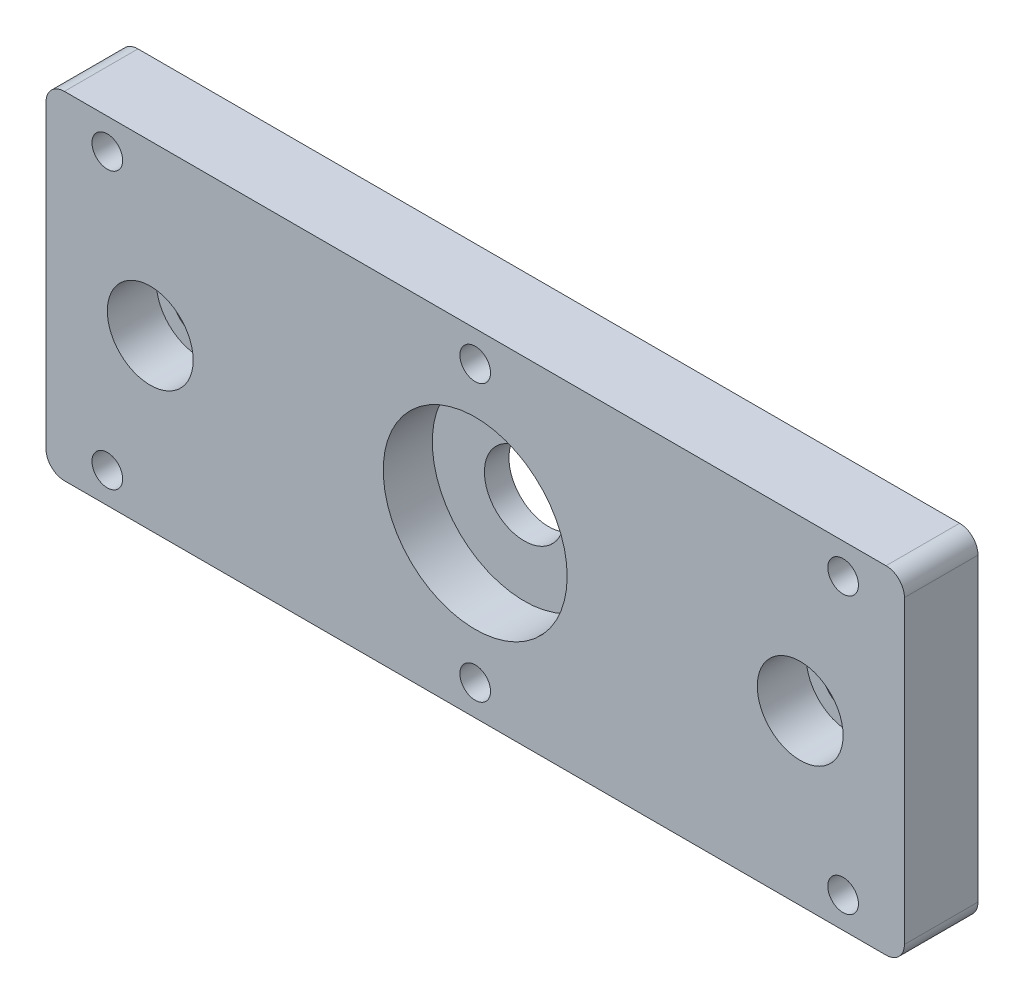
SolidWorks part; units mm, degrees
ref_plane "Front" through (0, 0, 0) normal (0, 0, 1) x (1, 0, 0)
ref_plane "Top" through (0, 0, 0) normal (0, 1, 0) x (1, 0, 0)
ref_plane "Right" through (0, 0, 0) normal (1, 0, 0) x (0, 0, -1)
sketch "草图1" plane through (0, 0, 0) normal (0, 0, 1) x (1, 0, 0)
  line L1 (-70, -27.5) -> (70, -27.5)
  line L2 (-70, -27.5) -> (-70, 27.5)
  line L3 (-70, 27.5) -> (70, 27.5)
  line L4 (70, -27.5) -> (70, 27.5)
  line L5 (-70, -27.5) -> (70, 27.5) construction
  line L6 (-70, 27.5) -> (70, -27.5) construction
  point P0 (0, 0)
  dimension "D1" = 55
  dimension "D2" = 140
extrude "凸台-拉伸1" add sketch "草图1" along normal blind 12
sketch "草图2" plane through (0, 0, 12) normal (0, 0, 1) x (1, 0, 0)
  line L0 (-70, 27.5) -> (-70, -27.5) construction
  line L1 (70, -27.5) -> (70, 27.5) construction
  circle A0 centre (0, 0) radius 6.5
  circle A1 centre (-53, 0) radius 4.5
  circle A2 centre (53, 0) radius 4.5
  dimension "D1" = 13
  dimension "D2" = 9
  dimension "D3" = 9
  dimension "D4" = 17
  dimension "D5" = 17
extrude "切除-拉伸1" cut sketch "草图2" against normal through all
fillet "圆角1" radius 3 4 edges at (70, 27.5, 6) (70, -27.5, 6) (-70, -27.5, 6) (-70, 27.5, 6)
sketch "草图10" plane through (0, 0, 12) normal (0, 0, 1) x (1, 0, 0)
  circle A0 centre (-53, 0) radius 7
  circle A1 centre (53, 0) radius 7
  dimension "D1" = 14
  dimension "D2" = 14
extrude "切除-拉伸2" cut sketch "草图10" against normal blind 8
sketch "草图11" plane through (0, 0, 12) normal (0, 0, 1) x (1, 0, 0)
  circle A0 centre (0, 0) radius 15
  dimension "D1" = 30
extrude "切除-拉伸3" cut sketch "草图11" against normal blind 8
sketch "草图12" plane through (0, 0, 12) normal (0, 0, 1) x (1, 0, 0)
  line L1 (-60, -22.5) -> (60, -22.5) construction
  line L2 (-60, -22.5) -> (-60, 22.5) construction
  line L3 (-60, 22.5) -> (60, 22.5) construction
  line L4 (60, -22.5) -> (60, 22.5) construction
  line L5 (-60, -22.5) -> (60, 22.5) construction
  line L6 (-60, 22.5) -> (60, -22.5) construction
  point P0 (0, 0)
  dimension "D1" = 120
  dimension "D2" = 45
hole_wizard "M6 螺纹孔1" positions "草图13" profile "草图14" tap size "M6" standard "GB" end condition through all
sketch "草图13" plane through (0, 0, 12) normal (0, 0, 1) x (1, 0, 0)
  line L0 (-60, -22.5) -> (60, -22.5) construction
  line L1 (-60, 22.5) -> (60, 22.5) construction
  point P0 (-60, 22.5)
  point P3 (-60, -22.5)
  point P6 (0, -22.5)
  point P10 (0, 22.5)
  point P14 (60, 22.5)
  point P17 (60, -22.5)
sketch "草图14" plane through (-60, 22.5, 12) normal (1, 0, 0) x (0, -1, 0)
  line L0 (0, 0) -> (0, 12)
  line L1 (0, 12) -> (2.5, 12)
  line L2 (2.5, 12) -> (2.5, 0)
  line L5 (2.5, 0) -> (0, 0)
  line L11 (0, -6.35) -> (0, 107.95) construction
  dimension "通孔螺纹孔钻头直径" = 5
  dimension "通孔螺纹孔钻头深度" = 12
cosmetic thread "孔螺蚊线9" parameters "D2"=6
cosmetic thread "孔螺蚊线10" parameters "D2"=6
cosmetic thread "孔螺蚊线11" parameters "D2"=6
cosmetic thread "孔螺蚊线12" parameters "D2"=6
cosmetic thread "孔螺蚊线13" parameters "D2"=6
cosmetic thread "孔螺蚊线14" parameters "D2"=6
